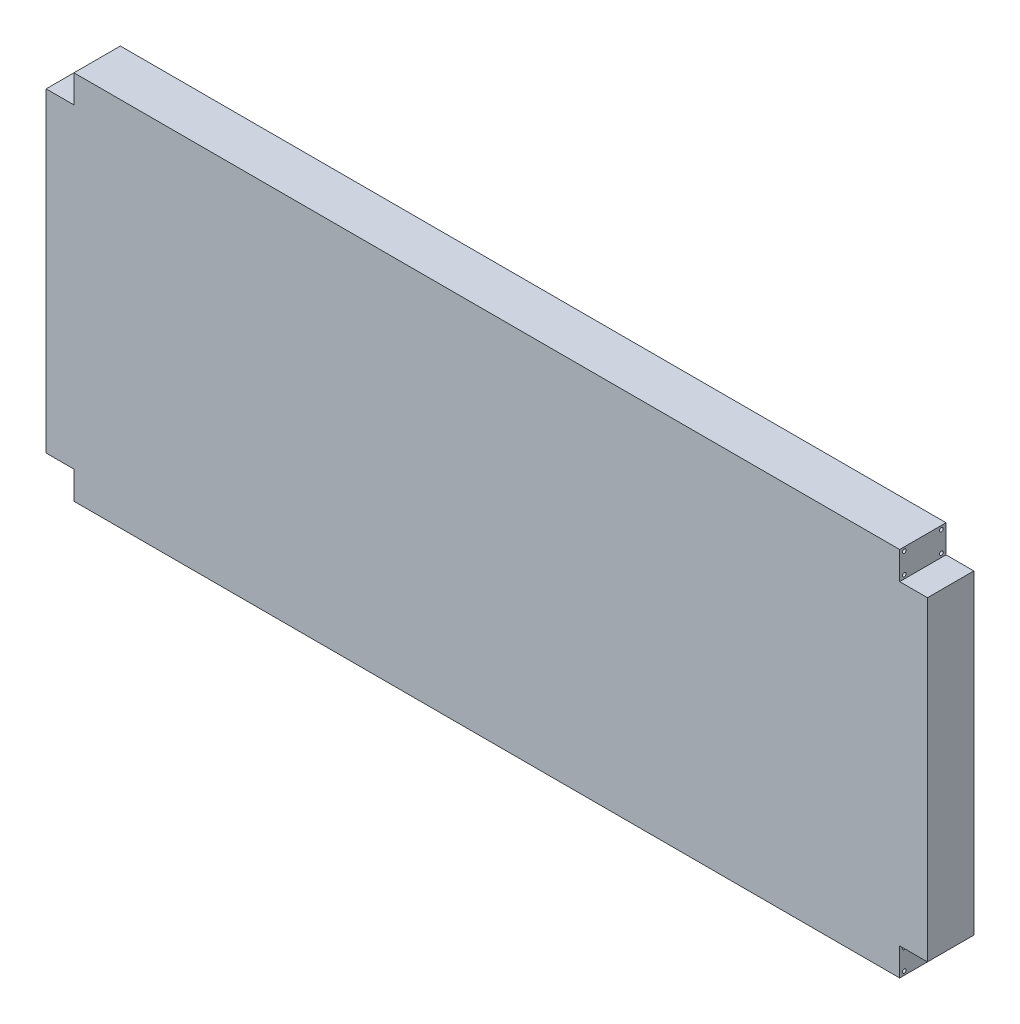
SolidWorks part; units mm, degrees
ref_plane "Front Plane" through (0, 0, 0) normal (0, 0, 1) x (1, 0, 0)
ref_plane "Top Plane" through (0, 0, 0) normal (0, 1, 0) x (1, 0, 0)
ref_plane "Right Plane" through (0, 0, 0) normal (1, 0, 0) x (0, 0, -1)
sketch "Sketch1" plane through (0, 0, 0) normal (0, 0, 1) x (1, 0, 0)
  line L1 (-475, 200) -> (475, 200)
  line L2 (-475, 200) -> (-475, -200)
  line L3 (-475, -200) -> (475, -200)
  line L4 (475, 200) -> (475, -200)
  line L5 (-475, 200) -> (475, -200) construction
  line L6 (-475, -200) -> (475, 200) construction
  point P0 (0, 0)
  dimension "D1" = 950
  dimension "D2" = 400
extrude "Boss-Extrude1" add sketch "Sketch1" along normal blind 50
sketch "Sketch2" plane through (0, 0, 50) normal (0, 0, 1) x (1, 0, 0)
  line L1 (-475, 200) -> (-445, 200)
  line L2 (-475, 200) -> (-475, 170)
  line L3 (-475, 170) -> (-445, 170)
  line L4 (-445, 200) -> (-445, 170)
  line L5 (-475, -200) -> (-445, -200)
  line L6 (-475, -200) -> (-475, -170)
  line L7 (-475, -170) -> (-445, -170)
  line L8 (-445, -200) -> (-445, -170)
  line L9 (475, -200) -> (445, -200)
  line L10 (475, -200) -> (475, -170)
  line L11 (475, -170) -> (445, -170)
  line L12 (445, -200) -> (445, -170)
  line L13 (475, 200) -> (445, 200)
  line L14 (475, 200) -> (475, 170)
  line L15 (475, 170) -> (445, 170)
  line L16 (445, 200) -> (445, 170)
  dimension "D1" = 30
  dimension "D2" = 30
  dimension "D3" = 30
  dimension "D4" = 30
  dimension "D5" = 30
  dimension "D6" = 30
  dimension "D7" = 30
  dimension "D8" = 30
extrude "Cut-Extrude1" cut sketch "Sketch2" against normal through all
hole_wizard "Ø4.0mm Dowel Hole1" positions "3DSketch2" profile "Sketch4" hole size "Ø4.0" standard "ANSI Metric"
sketch3d "3DSketch2"
  line L0 (445, -200, 0) -> (445, -200, 50) construction
  line L1 (445, -170, 50) -> (445, -200, 50) construction
  line L2 (445, -170, 0) -> (445, -170, 50) construction
  line L3 (445, -170, 0) -> (445, -200, 0) construction
  point P0 (445, -196, 45)
  point P2 (445, -174, 45)
  point P4 (445, -196, 5)
  point P6 (445, -174, 5)
  dimension "D1" = 4
  dimension "D2" = 5
  dimension "D3" = 5
  dimension "D4" = 4
  dimension "D5" = 5
  dimension "D6" = 4
  dimension "D7" = 5
  dimension "D8" = 4
sketch "Sketch4" plane through (445, -196, 45) normal (0, 1, 0) x (0, 0, -1)
  line L0 (0, 0) -> (0, 31.2017)
  line L1 (0, 31.2017) -> (2, 30)
  line L2 (2, 30) -> (2, 0)
  line L5 (2, 0) -> (0, 0)
  line L10 (0, 31.2017) -> (-2, 30) construction
  line L11 (0, -6.35) -> (0, 107.95) construction
  dimension "Hole Dia." = 4
  dimension "Hole Depth" = 30
  dimension "Drill Angle" = 118
hole_wizard "Ø4.0mm Dowel Hole2" positions "3DSketch3" profile "Sketch5" hole size "Ø4.0" standard "ANSI Metric"
sketch3d "3DSketch3"
  line L0 (-445, -200, 0) -> (-445, -170, 0) construction
  line L1 (-445, -200, 0) -> (-445, -200, 50) construction
  line L4 (-445, -170, 0) -> (-445, -170, 50) construction
  line L5 (-445, -200, 50) -> (-445, -170, 50) construction
  point P0 (-445, -174, 5)
  point P2 (-445, -174, 45)
  point P4 (-445, -196, 45)
  point P6 (-445, -196, 5)
  dimension "D1" = 5
  dimension "D2" = 5
  dimension "D3" = 4
  dimension "D4" = 4
  dimension "D5" = 5
  dimension "D6" = 5
  dimension "D7" = 4
  dimension "D8" = 4
sketch "Sketch5" plane through (-445, -174, 5) normal (0, 1, 0) x (0, 0, 1)
  line L0 (0, 0) -> (0, 31.2017)
  line L1 (0, 31.2017) -> (2, 30)
  line L2 (2, 30) -> (2, 0)
  line L5 (2, 0) -> (0, 0)
  line L10 (0, 31.2017) -> (-2, 30) construction
  line L11 (0, -6.35) -> (0, 107.95) construction
  dimension "Hole Dia." = 4
  dimension "Hole Depth" = 30
  dimension "Drill Angle" = 118
hole_wizard "Ø4.0mm Dowel Hole3" positions "3DSketch4" profile "Sketch6" hole size "Ø4.0" standard "ANSI Metric"
sketch3d "3DSketch4"
  line L0 (-445, 170, 50) -> (-445, 200, 50) construction
  line L1 (-445, 170, 0) -> (-445, 200, 0) construction
  line L2 (-445, 200, 0) -> (-445, 200, 50) construction
  line L3 (-445, 170, 0) -> (-445, 170, 50) construction
  point P0 (-445, 174, 45)
  point P2 (-445, 196, 45)
  point P4 (-445, 196, 5)
  point P6 (-445, 174, 5)
  dimension "D1" = 5
  dimension "D2" = 5
  dimension "D3" = 5
  dimension "D4" = 5
  dimension "D5" = 4
  dimension "D6" = 4
  dimension "D7" = 4
  dimension "D8" = 4
sketch "Sketch6" plane through (-445, 174, 45) normal (0, 1, 0) x (0, 0, 1)
  line L0 (0, 0) -> (0, 31.2017)
  line L1 (0, 31.2017) -> (2, 30)
  line L2 (2, 30) -> (2, 0)
  line L5 (2, 0) -> (0, 0)
  line L10 (0, 31.2017) -> (-2, 30) construction
  line L11 (0, -6.35) -> (0, 107.95) construction
  dimension "Hole Dia." = 4
  dimension "Hole Depth" = 30
  dimension "Drill Angle" = 118
hole_wizard "Ø4.0mm Dowel Hole4" positions "3DSketch5" profile "Sketch7" hole size "Ø4.0" standard "ANSI Metric"
sketch3d "3DSketch5"
  line L0 (445, 200, 50) -> (445, 170, 50) construction
  line L1 (445, 200, 0) -> (445, 170, 0) construction
  line L2 (445, 200, 0) -> (445, 200, 50) construction
  line L3 (445, 170, 0) -> (445, 170, 50) construction
  point P0 (445, 174, 45)
  point P2 (445, 196, 45)
  point P4 (445, 174, 5)
  point P6 (445, 196, 5)
  dimension "D1" = 5
  dimension "D2" = 5
  dimension "D3" = 5
  dimension "D4" = 5
  dimension "D5" = 4
  dimension "D6" = 4
  dimension "D7" = 4
  dimension "D8" = 4
sketch "Sketch7" plane through (445, 174, 45) normal (0, 1, 0) x (0, 0, -1)
  line L0 (0, 0) -> (0, 31.2017)
  line L1 (0, 31.2017) -> (2, 30)
  line L2 (2, 30) -> (2, 0)
  line L5 (2, 0) -> (0, 0)
  line L10 (0, 31.2017) -> (-2, 30) construction
  line L11 (0, -6.35) -> (0, 107.95) construction
  dimension "Hole Dia." = 4
  dimension "Hole Depth" = 30
  dimension "Drill Angle" = 118
